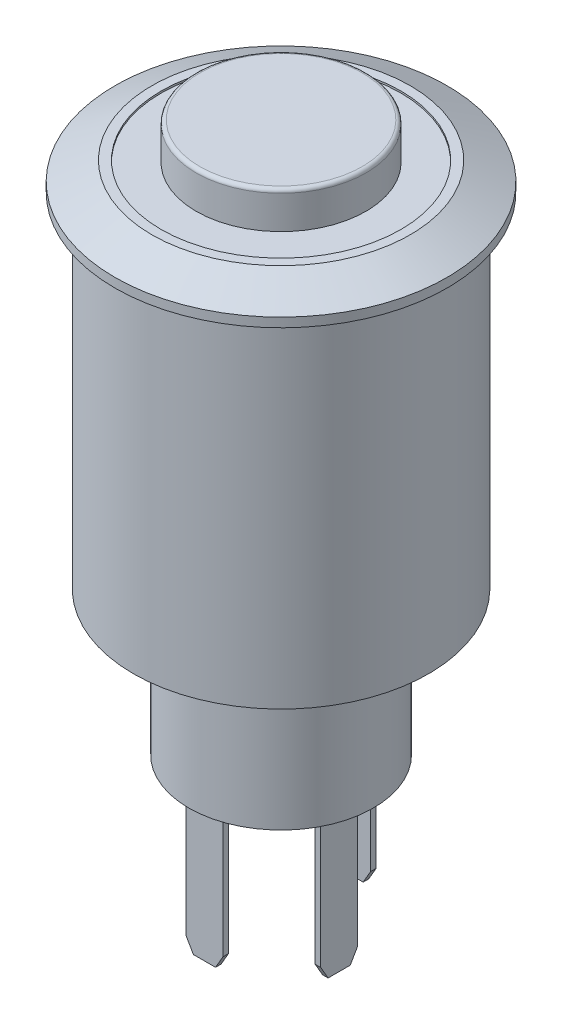
SolidWorks part; units mm, degrees
ref_plane "Front Plane" through (0, 0, 0) normal (0, 0, 1) x (1, 0, 0)
ref_plane "Top Plane" through (0, 0, 0) normal (0, 1, 0) x (1, 0, 0)
ref_plane "Right Plane" through (0, 0, 0) normal (1, 0, 0) x (0, 0, -1)
sketch "Sketch1" plane through (0, 0, 0) normal (1, 0, 0) x (0, 0, -1)
  line L1 (0, 3.4) -> (-4.6, 3.4)
  line L2 (-4.6, 3.4) -> (-4.6, 1.5)
  line L3 (-4.6, 1.5) -> (-7, 1.5)
  line L4 (-7, 1.5) -> (-9, 0.5)
  line L5 (-9, 0.5) -> (-9, 0)
  line L6 (-9, 0) -> (-8, 0)
  line L7 (-8, 0) -> (-8, -18.6)
  line L8 (-8, -18.6) -> (-5, -18.6)
  line L9 (-5, -18.6) -> (-5, -26.4)
  line L10 (-5, -26.4) -> (0, -26.4)
  line L11 (0, 14.375) -> (0, -32.104) construction
  line L12 (0, 3.4) -> (0, -26.4)
  dimension "D1" = 9.2
  dimension "D2" = 18
  dimension "D3" = 16
  dimension "D4" = 10
  dimension "D5" = 27.9
  dimension "D6" = 20.1
  dimension "D7" = 1.5
  dimension "D8" = 14
  dimension "D9" = 0.5
  dimension "D10" = 1.9
revolve "Revolve1" add sketch "Sketch1" angle 360 about L11
fillet "Fillet1" radius 0.2 1 edges at (0, 3.4, 4.6)
sketch "Sketch2" plane through (0, 1.5, 0) normal (0, 1, 0) x (1, 0, 0)
  circle A0 centre (0, 0) radius 4.6
  circle A1 centre (0, 0) radius 6.5
  circle A2 centre (0, 0) radius 4.6 construction
  dimension "D1" = 13
extrude "Cut-Extrude1" cut sketch "Sketch2" against normal blind 0.1
sketch "Sketch3" plane through (0, -26.4, 0) normal (0, -1, 0) x (1, 0, 0)
  line L0 (-1, 4) -> (1, 4)
  line L1 (-1, -4) -> (1, -4)
  line L2 (-1, 4) -> (1, -4) construction
  line L3 (-4, 1) -> (-4, -1)
  line L4 (4, 0) -> (4, 2)
  line L5 (-4, 0) -> (0, 0) construction
  point P12 (4, 1)
  dimension "D1" = 8
  dimension "D2" = 2
  dimension "D3" = 8
  dimension "D4" = 1
  dimension "D5" = 4
extrude "Extrude-Thin1" add sketch "Sketch3" along normal blind 7.6 thin thin type mid plane wall 0.3
chamfer "Chamfer1" distance 0.4 angle 60 8 edges at (1, -34, 4) (-1, -34, 4) (-4, -34, 1) (-4, -34, -1) (-1, -34, -4) (1, -34, -4) (4, -34, 0) (4, -34, 2)
